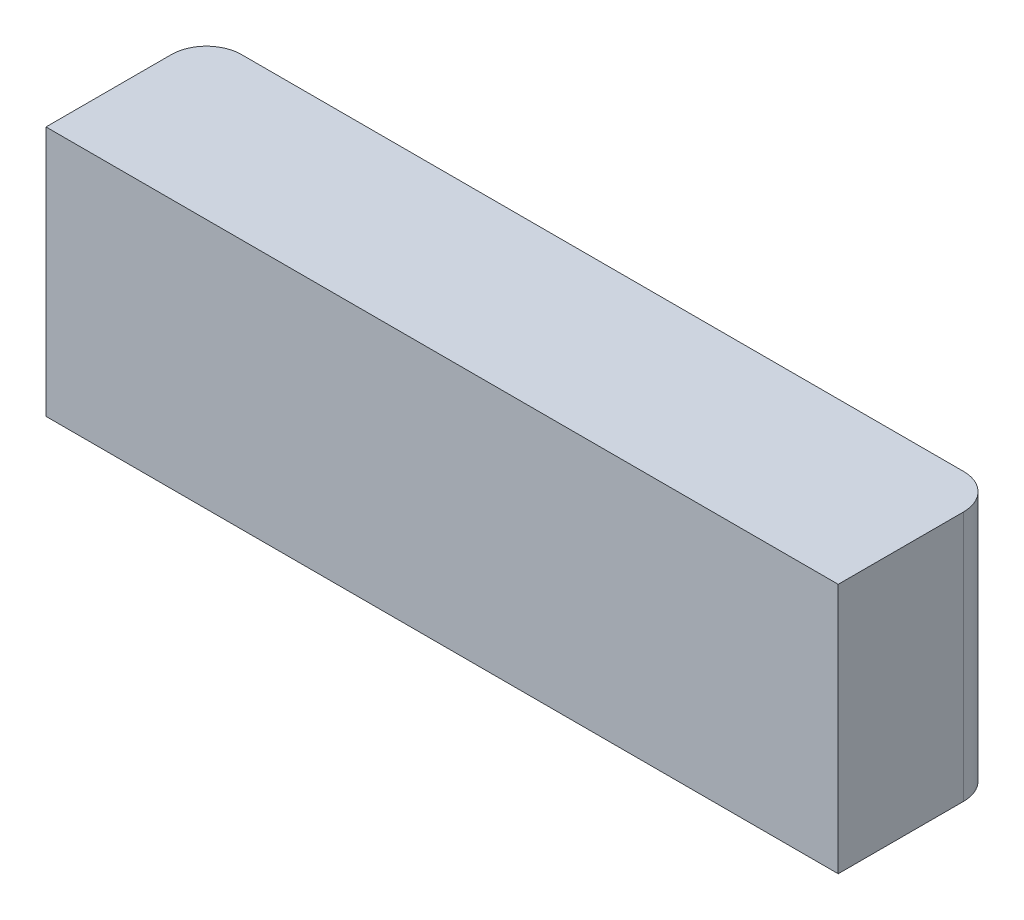
SolidWorks part; units mm, degrees
ref_plane "Front" through (0, 0, 0) normal (0, 0, 1) x (1, 0, 0)
ref_plane "Top" through (0, 0, 0) normal (0, 1, 0) x (1, 0, 0)
ref_plane "Right" through (0, 0, 0) normal (1, 0, 0) x (0, 0, -1)
other "Configuration Table"
sketch "Sketch1" plane through (0, 0, 0) normal (0, 1, 0) x (1, 0, 0)
  line L1 (-108, 24) -> (108, 24)
  line L2 (-118.5, 13.5) -> (-118.5, -24)
  line L3 (-118.5, -24) -> (118.5, -24)
  line L4 (118.5, 13.5) -> (118.5, -24)
  line L5 (-118.5, 24) -> (118.5, -24) construction
  line L6 (-118.5, -24) -> (118.5, 24) construction
  arc A0 (118.5, 13.5) -> (108, 24) centre (108, 13.5) ccw
  arc A1 (-108, 24) -> (-118.5, 13.5) centre (-108, 13.5) ccw
  point P0 (0, 0)
  dimension "D3" = 10.5
  dimension "D1" = 237
  dimension "D2" = 48
extrude "Boss-Extrude1" add sketch "Sketch1" along normal mid plane 75
